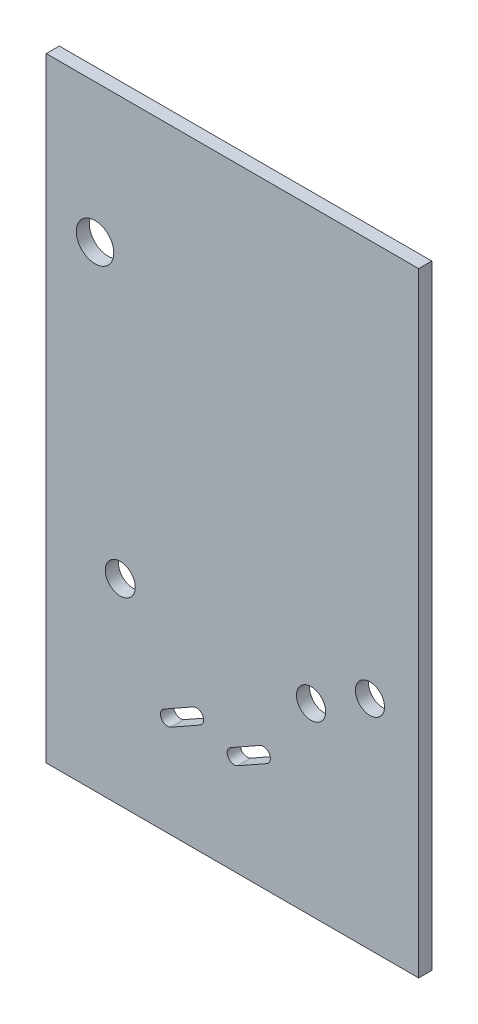
SolidWorks part; units mm, degrees
ref_plane "Front Plane" through (0, 0, 0) normal (0, 0, 1) x (1, 0, 0)
ref_plane "Top Plane" through (0, 0, 0) normal (0, 1, 0) x (1, 0, 0)
ref_plane "Right Plane" through (0, 0, 0) normal (1, 0, 0) x (0, 0, -1)
sketch "Sketch1" plane through (0, 0, 0) normal (0, 0, 1) x (1, 0, 0)
  line L1 (-26.2308, 73.6471) -> (38.6518, 73.6471)
  line L3 (-44.6471, -70.649) -> (-44.6471, 70.649)
  line L5 (27.0934, -73.6471) -> (-41.649, -73.6471)
  line L7 (-24.0867, 73.6955) -> (-35.6911, 73.6955)
  line L15 (-16.3293, -29.1587) -> (-16.3293, -23.8757)
  line L19 (44.6471, 67.6705) -> (44.6471, -53.896)
  line L20 (-0.4012, -48.3225) -> (6.5714, -44.4005)
  line L21 (8.2266, -47.343) -> (1.254, -51.2651)
  line L22 (-44.6471, 73.6471) -> (44.6471, 73.6471)
  line L23 (44.6471, 73.6471) -> (44.6471, -73.6471)
  line L24 (44.6471, -73.6471) -> (-44.6471, -73.6471)
  line L25 (-44.6471, -73.6471) -> (-44.6471, 73.6471)
  line L26 (-25.1679, 56.2163) -> (-25.1679, 10.288)
  line L27 (-25.1679, 10.288) -> (24.9222, 10.288)
  line L28 (24.9222, 10.288) -> (24.9222, 56.2163)
  line L29 (24.9222, 56.2163) -> (-25.1679, 56.2163)
  line L34 (36.6393, 62.5051) -> (-36.0272, 62.5051)
  line L35 (-38.5272, 60.0051) -> (-38.5272, 6.9331)
  line L36 (-36.0272, 4.4331) -> (29.8893, 4.4331)
  line L37 (39.1393, 13.6831) -> (39.1393, 60.0051)
  line L38 (-16.4012, -48.3225) -> (-9.4286, -44.4005)
  line L39 (-7.7734, -47.343) -> (-14.746, -51.2651)
  line L41 (44.6471, 70.649) -> (44.6471, 67.6705)
  line L43 (38.6518, 73.6471) -> (41.649, 73.6471)
  line L45 (-41.649, 73.6471) -> (-26.2308, 73.6471)
  line L150 (42.2525, -55.0539) -> (42.2511, -54.9499)
  circle A0 centre (34.1495, 24.0914) radius 10.7
  circle A2 centre (-26.9008, -26.5172) radius 3.6
  arc A3 (8.2266, -47.343) -> (6.5714, -44.4005) centre (7.399, -45.8717) ccw
  arc A6 (-16.4012, -48.3225) -> (-14.746, -51.2651) centre (-15.5736, -49.7938) ccw
  arc A7 (-7.7734, -47.343) -> (-9.4286, -44.4005) centre (-8.601, -45.8717) ccw
  circle A15 centre (18.8495, -29.5462) radius 3.5
  circle A16 centre (32.9602, -21.4767) radius 3.5
  arc A17 (-0.4012, -48.3225) -> (1.254, -51.2651) centre (0.4264, -49.7938) ccw
  circle A19 centre (-32.9539, 40.3411) radius 4.5
  arc A24 (39.1393, 60.0051) -> (36.6393, 62.5051) centre (36.6393, 60.0051) ccw
  arc A25 (-36.0272, 62.5051) -> (-38.5272, 60.0051) centre (-36.0272, 60.0051) ccw
  arc A26 (-38.5272, 6.9331) -> (-36.0272, 4.4331) centre (-36.0272, 6.9331) ccw
  arc A27 (29.8893, 4.4331) -> (39.1393, 13.6831) centre (29.8893, 13.6831) ccw
  ellipse E3 centre (-41.649, -70.649) end of major axis (-39.5276, -72.7703) minor radius 2.9963 (-44.6471, -70.649) -> (-41.649, -73.6471) ccw
  ellipse E5 centre (41.649, 70.649) end of major axis (39.5276, 72.7703) minor radius 2.9963 (44.6471, 70.649) -> (41.649, 73.6471) ccw
  ellipse E7 centre (-41.649, 70.649) end of major axis (-43.7703, 68.5276) minor radius 2.9963 (-41.649, 73.6471) -> (-44.6471, 70.649) ccw
  spline S1 degree 3 poles (44.6485, -54) (44.663, -55.258) (44.5568, -56.5068) (44.2157, -58.3662) (44.0715, -58.9837) (43.7192, -60.2138) (43.5128, -60.8202) (42.8075, -62.6008) (42.2221, -63.7422) (41.3373, -65.1085) (41.1525, -65.3788) (40.7717, -65.907) (40.5751, -66.1657) (39.9672, -66.9256) (39.1083, -67.8961) (38.1523, -68.7812) (37.1464, -69.6222) (36.6152, -70.0225) (34.9811, -71.1285) (33.8311, -71.748) (32.3187, -72.3766) (32.0124, -72.495) (31.3922, -72.7168) (31.0776, -72.8204) (30.1333, -73.105) (29.5001, -73.2613) (27.5898, -73.6337) (26.302, -73.7542) (25, -73.7456) knots 0 0 0 0 0.125 0.125 0.1875 0.1875 0.25 0.25 0.375 0.375 0.40625 0.40625 0.4375 0.4375 0.5 0.5625 0.5625 0.625 0.625 0.75 0.75 0.78125 0.78125 0.8125 0.8125 0.875 0.875 1 1 1 1
  dimension "D4" = 21.4
  dimension "D8" = 7
  dimension "D11" = 9
  dimension "D12" = 7.2
  dimension "D1" = 10.4977
  dimension "D2" = 89.2943
  dimension "D3" = 147.2943
  dimension "D5" = 25.9097
  dimension "D6" = 8.0696
  dimension "D7" = 14.1107
  dimension "D9" = 7.7861
  dimension "D10" = 22.1641
  dimension "D13" = 10.5715
extrude "Boss-Extrude1" add sketch "Sketch1" along normal blind 3.14
